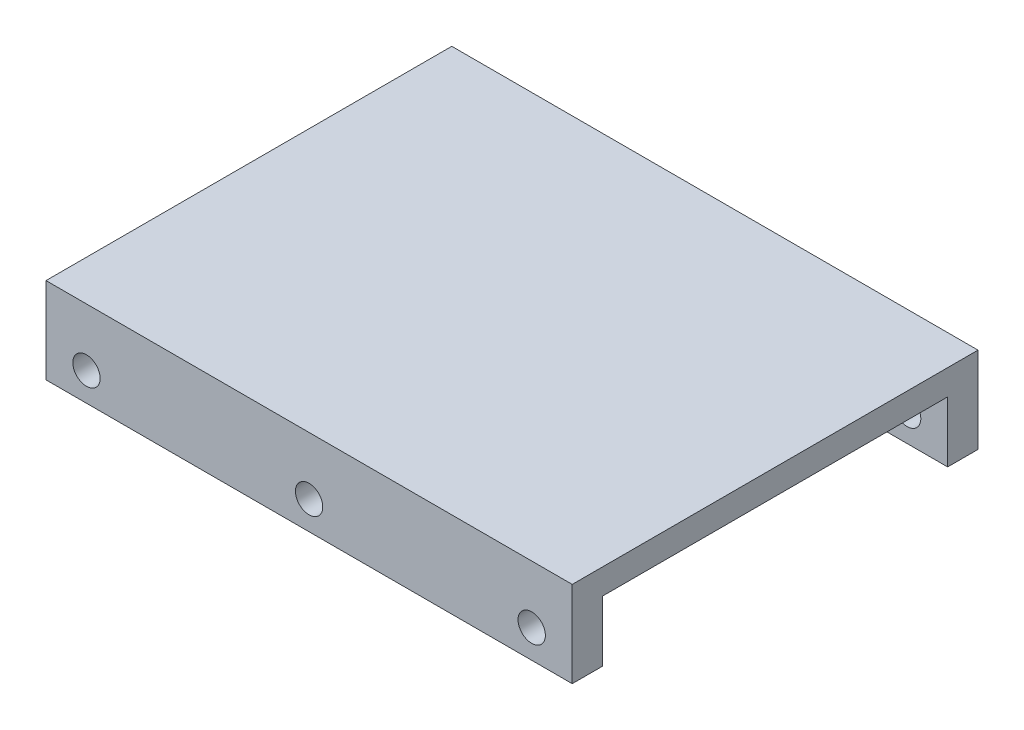
SolidWorks part; units mm, degrees
material "ABS PC"
ref_plane "Front Plane" through (0, 0, 0) normal (0, 0, 1) x (1, 0, 0)
ref_plane "Top Plane" through (0, 0, 0) normal (0, 1, 0) x (1, 0, 0)
ref_plane "Right Plane" through (0, 0, 0) normal (1, 0, 0) x (0, 0, -1)
sketch "Sketch1" plane through (0, 0, 0) normal (0, 0, 1) x (1, 0, 0)
  line L0 (0, 0) -> (0, 52.578)
  line L1 (0, 52.578) -> (6, 52.578)
  line L2 (6, 52.578) -> (6, 8.5)
  line L3 (6, 8.5) -> (76, 8.5)
  line L4 (76, 8.5) -> (76, 0)
  line L5 (76, 0) -> (0, 0)
  dimension "D1" = 52.578
  dimension "D2" = 8.5
  dimension "D3" = 6
  dimension "D4" = 76
extrude "Boss-Extrude1" add sketch "Sketch1" along normal blind 40.1
sketch "Sketch3" plane through (0, 0, 40.1) normal (0, 0, 1) x (1, 0, 0)
  line L0 (0, 52.578) -> (0, 0) construction
  line L1 (0, 0) -> (76, 0) construction
  circle A0 centre (27.996, 2.8) radius 1.35
  circle A1 centre (49.996, 2.8) radius 1.35
  circle A2 centre (71.996, 2.8) radius 1.35
  dimension "D1" = 2.7
  dimension "D4" = 2.7
  dimension "D5" = 2.7
  dimension "D2" = 27.996
  dimension "D3" = 2.8
  dimension "D6" = 22
  dimension "D7" = 22
extrude "Cut-Extrude2" cut sketch "Sketch3" against normal blind 50.8
sketch "Sketch4" plane through (0, 0, 0) normal (-1, 0, 0) x (0, 0, 1)
  line L0 (40.1, 0) -> (0, 0) construction
  line L1 (20.05, 0) -> (20.05, 52.578) construction
  line L2 (40.1, 52.578) -> (0, 52.578) construction
  line L3 (40.1, 52.578) -> (40.1, 0) construction
  line L5 (0, 52.578) -> (0, 0) construction
  circle A0 centre (27.88, 17.6) radius 1.016
  circle A1 centre (11.88, 17.6) radius 1.016
  circle A2 centre (27.88, 49.6) radius 1.016
  circle A3 centre (11.88, 49.6) radius 1.016
  dimension "D1" = 2.032
  dimension "D3" = 2.032
  dimension "D4" = 2.978
  dimension "D2" = 17.6
  dimension "D5" = 12.22
  dimension "D6" = 12.22
  dimension "D7" = 11.88
  dimension "D8" = 11.88
  dimension "D9" = 2.978
extrude "Cut-Extrude3" cut sketch "Sketch4" against normal blind 50.8
sketch "Sketch6" plane through (0, 0, 0) normal (0, -1, 0) x (1, 0, 0)
  line L0 (0, 40.1) -> (76, 40.1) construction
  line L1 (19, 37.1) -> (81.0861, 37.1)
  line L2 (19, 37.1) -> (19, 3)
  line L3 (19, 3) -> (81.0861, 3)
  line L4 (81.0861, 37.1) -> (81.0861, 3)
  line L5 (0, 0) -> (76, 0) construction
  line L6 (0, 40.1) -> (0, 0) construction
  dimension "D1" = 3
  dimension "D2" = 3
  dimension "D3" = 19
extrude "Cut-Extrude4" cut sketch "Sketch6" against normal blind 6
ref_plane "Plane5" through (0, 0, 20.05) normal (0, 0, -1) x (-1, 0, 0)
sketch "Sketch17" plane through (0, 0, 40.1) normal (0, 0, 1) x (1, 0, 0)
  line L0 (1, 0) -> (75, 0) construction
  line L1 (23.996, 0) -> (-9.4877, 0)
  line L2 (23.996, 0) -> (23.996, 71.7627)
  line L3 (23.996, 71.7627) -> (-9.4877, 71.7627)
  line L4 (-9.4877, 0) -> (-9.4877, 71.7627)
  circle A0 centre (27.996, 2.8) radius 1.35 construction
  dimension "D1" = 4
extrude "Cut-Extrude5" cut sketch "Sketch17" against normal through all
